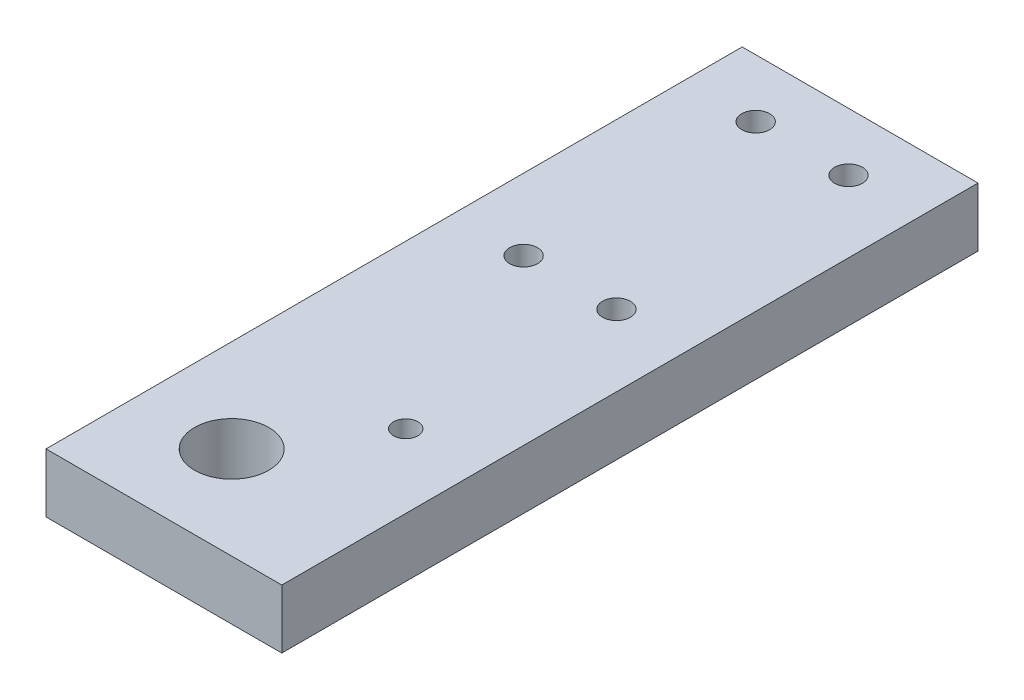
SolidWorks part; units mm, degrees
ref_plane "Front Plane" through (0, 0, 0) normal (0, 0, 1) x (1, 0, 0)
ref_plane "Top Plane" through (0, 0, 0) normal (0, 1, 0) x (1, 0, 0)
ref_plane "Right Plane" through (0, 0, 0) normal (1, 0, 0) x (0, 0, -1)
sketch "Sketch2" plane through (0, 0, 0) normal (0, 1, 0) x (1, 0, 0)
  line L1 (0, 0) -> (101.6, 0)
  line L2 (0, 0) -> (0, 300)
  line L3 (0, 300) -> (101.6, 300)
  line L4 (101.6, 0) -> (101.6, 300)
  dimension "D1" = 101.6
  dimension "D2" = 300
extrude "Boss-Extrude1" add sketch "Sketch2" along normal blind 25.4
sketch "Sketch3" plane through (0, 25.4, 0) normal (0, 1, 0) x (1, 0, 0)
  line L1 (0, 300) -> (50.8, 300)
  line L2 (0, 300) -> (0, 225)
  line L3 (0, 225) -> (50.8, 225)
  line L4 (50.8, 300) -> (50.8, 225)
  line L5 (30.8, 175) -> (70.8, 175)
  line L6 (30.8, 175) -> (30.8, 275)
  line L7 (30.8, 275) -> (70.8, 275)
  line L8 (70.8, 175) -> (70.8, 275)
  line L9 (30.8, 175) -> (70.8, 275) construction
  line L10 (30.8, 275) -> (70.8, 175) construction
  circle A0 centre (70.8, 275) radius 6
  circle A1 centre (30.8, 275) radius 6
  circle A2 centre (30.8, 175) radius 6
  circle A3 centre (70.8, 175) radius 6
  dimension "D1" = 50.8
  dimension "D2" = 75
  dimension "D3" = 40
  dimension "D4" = 100
extrude "Cut-Extrude1" cut sketch "Sketch3" against normal blind 25.4 contours A1 | A0 | A3 | A2
sketch "Sketch4" plane through (0, 25.4, 0) normal (0, 1, 0) x (1, 0, 0)
  line L1 (0, 300) -> (40, 300)
  line L2 (0, 300) -> (0, 40)
  line L3 (0, 40) -> (40, 40)
  line L4 (40, 300) -> (40, 40)
  circle A0 centre (40, 40) radius 16
  dimension "D1" = 260
  dimension "D2" = 40
extrude "Cut-Extrude2" cut sketch "Sketch4" against normal blind 25.4 contours A0
sketch "Sketch5" plane through (0, 25.4, 0) normal (0, 1, 0) x (1, 0, 0)
  line L1 (0, 300) -> (70, 300)
  line L2 (0, 300) -> (0, 85)
  line L3 (0, 85) -> (70, 85)
  line L4 (70, 300) -> (70, 85)
  circle A0 centre (70, 85) radius 5.25
  dimension "D1" = 215
  dimension "D2" = 70
extrude "Cut-Extrude3" cut sketch "Sketch5" against normal blind 25.4 contours A0
